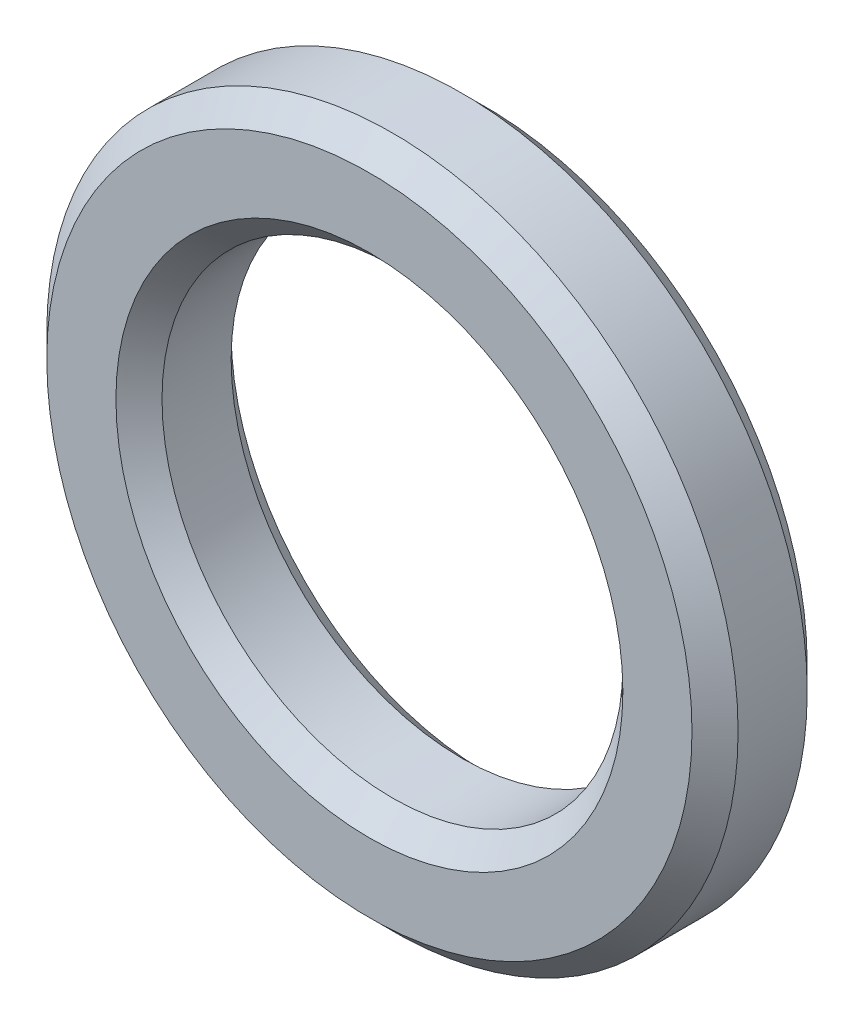
SolidWorks part; units mm, degrees
ref_plane "Front Plane" through (0, 0, 0) normal (0, 0, 1) x (1, 0, 0)
ref_plane "Top Plane" through (0, 0, 0) normal (0, 1, 0) x (1, 0, 0)
ref_plane "Right Plane" through (0, 0, 0) normal (1, 0, 0) x (0, 0, -1)
sketch "Sketch2" plane through (0, 0, 0) normal (0, 0, 1) x (1, 0, 0)
  circle A0 centre (0, 0) radius 10
  dimension "D1" = 20
extrude "Extrude-Thin1" add sketch "Sketch2" along normal blind 5 thin
chamfer "Chamfer1" distance 1 angle 45 4 edges at (10, 0, 0) (15, 0, 0) (15, 0, 5) (10, 0, 5)
